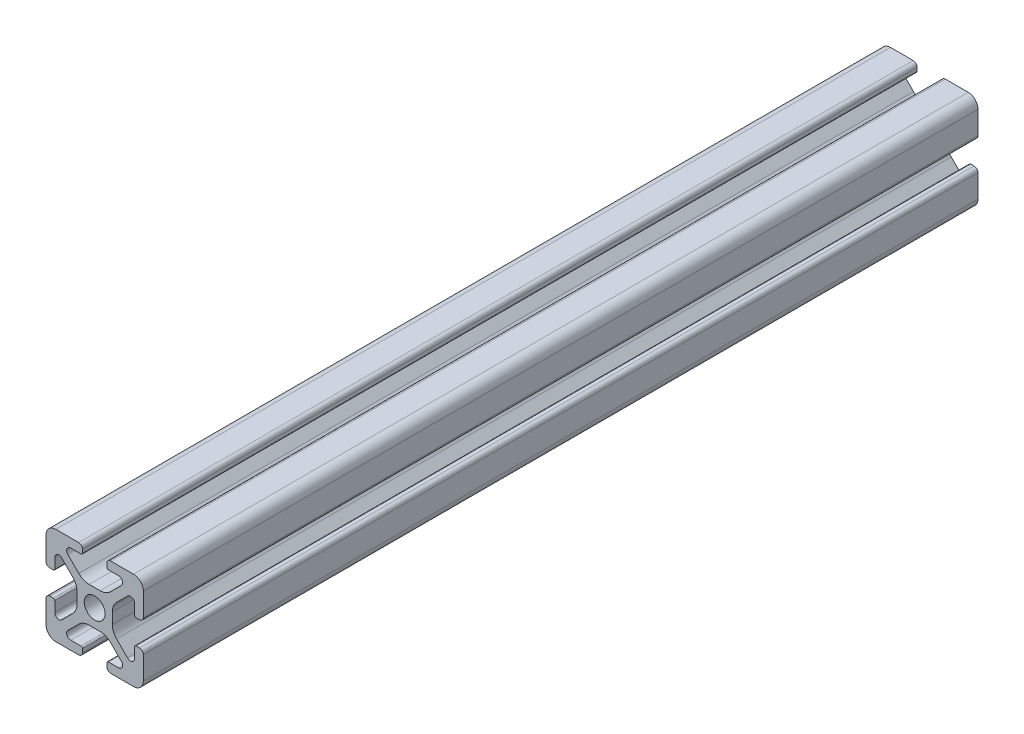
SolidWorks part; units mm, degrees
ref_plane "Front Plane" through (0, 0, 0) normal (0, 0, 1) x (1, 0, 0)
ref_plane "Top Plane" through (0, 0, 0) normal (0, 1, 0) x (1, 0, 0)
ref_plane "Right Plane" through (0, 0, 0) normal (1, 0, 0) x (0, 0, -1)
sketch "Sketch1" plane through (0, 0, 0) normal (0, 0, 1) x (1, 0, 0)
  line L2 (-9.9949, 7.9883) -> (-9.9949, 3.2893)
  line L3 (-7.9883, 9.9949) -> (-3.2893, 9.9949)
  line L4 (-2.5019, 9.2075) -> (-2.5019, 8.4963)
  line L5 (-2.8067, 8.1915) -> (-4.9149, 8.1915)
  line L6 (-5.5076, 6.7606) -> (-3.2528, 4.5058)
  line L7 (-6.7606, 5.5076) -> (-4.5058, 3.2528)
  line L8 (-8.1915, 4.9149) -> (-8.1915, 2.8067)
  line L9 (-8.4963, 2.5019) -> (-9.2075, 2.5019)
  line L11 (-1.1334, 3.6279) -> (1.1334, 3.6279)
  line L12 (-3.6279, 1.1334) -> (-3.6279, -1.1334)
  line L13 (8.4963, 2.5019) -> (9.2075, 2.5019)
  line L14 (8.1915, 4.9149) -> (8.1915, 2.8067)
  line L15 (9.9949, 7.9883) -> (9.9949, 3.2893)
  line L16 (7.9883, 9.9949) -> (3.2893, 9.9949)
  line L17 (2.5019, 9.2075) -> (2.5019, 8.4963)
  line L18 (2.8067, 8.1915) -> (4.9149, 8.1915)
  line L19 (3.6279, 1.1334) -> (3.6279, -1.1334)
  line L20 (5.5076, 6.7606) -> (3.2528, 4.5058)
  line L21 (6.7606, 5.5076) -> (4.5058, 3.2528)
  line L22 (-8.4963, -2.5019) -> (-9.2075, -2.5019)
  line L23 (-8.1915, -4.9149) -> (-8.1915, -2.8067)
  line L24 (-6.7606, -5.5076) -> (-4.5058, -3.2528)
  line L25 (-5.5076, -6.7606) -> (-3.2528, -4.5058)
  line L26 (-2.8067, -8.1915) -> (-4.9149, -8.1915)
  line L27 (-2.5019, -9.2075) -> (-2.5019, -8.4963)
  line L28 (-7.9883, -9.9949) -> (-3.2893, -9.9949)
  line L29 (-9.9949, -7.9883) -> (-9.9949, -3.2893)
  line L30 (9.9949, -7.9883) -> (9.9949, -3.2893)
  line L31 (7.9883, -9.9949) -> (3.2893, -9.9949)
  line L32 (2.5019, -9.2075) -> (2.5019, -8.4963)
  line L33 (2.8067, -8.1915) -> (4.9149, -8.1915)
  line L34 (5.5076, -6.7606) -> (3.2528, -4.5058)
  line L35 (6.7606, -5.5076) -> (4.5058, -3.2528)
  line L36 (8.1915, -4.9149) -> (8.1915, -2.8067)
  line L37 (8.4963, -2.5019) -> (9.2075, -2.5019)
  line L38 (-1.1334, -3.6279) -> (1.1334, -3.6279)
  circle A0 centre (0, 0) radius 2.1463
  arc A1 (-9.9949, 7.9883) -> (-7.9883, 9.9949) centre (-7.9883, 7.9883) cw
  arc A2 (-6.7606, 5.5076) -> (-8.1915, 4.9149) centre (-7.3533, 4.9149) ccw
  arc A3 (-4.9149, 8.1915) -> (-5.5076, 6.7606) centre (-4.9149, 7.3533) ccw
  arc A4 (-3.2893, 9.9949) -> (-2.5019, 9.2075) centre (-3.2893, 9.2075) cw
  arc A5 (-9.9949, 3.2893) -> (-9.2075, 2.5019) centre (-9.2075, 3.2893) ccw
  arc A6 (-8.1915, 2.8067) -> (-8.4963, 2.5019) centre (-8.4963, 2.8067) cw
  arc A7 (-2.5019, 8.4963) -> (-2.8067, 8.1915) centre (-2.8067, 8.4963) cw
  arc A8 (-1.1334, 3.6279) -> (-3.2528, 4.5058) centre (-1.1334, 6.6251) cw
  arc A9 (-3.6279, 1.1334) -> (-4.5058, 3.2528) centre (-6.6251, 1.1334) ccw
  arc A10 (8.1915, 2.8067) -> (8.4963, 2.5019) centre (8.4963, 2.8067) ccw
  arc A11 (9.9949, 3.2893) -> (9.2075, 2.5019) centre (9.2075, 3.2893) cw
  arc A12 (9.9949, 7.9883) -> (7.9883, 9.9949) centre (7.9883, 7.9883) ccw
  arc A13 (3.2893, 9.9949) -> (2.5019, 9.2075) centre (3.2893, 9.2075) ccw
  arc A14 (2.5019, 8.4963) -> (2.8067, 8.1915) centre (2.8067, 8.4963) ccw
  arc A15 (1.1334, 3.6279) -> (3.2528, 4.5058) centre (1.1334, 6.6251) ccw
  arc A16 (3.6279, 1.1334) -> (4.5058, 3.2528) centre (6.6251, 1.1334) cw
  arc A17 (6.7606, 5.5076) -> (8.1915, 4.9149) centre (7.3533, 4.9149) cw
  arc A18 (4.9149, 8.1915) -> (5.5076, 6.7606) centre (4.9149, 7.3533) cw
  arc A19 (-3.6279, -1.1334) -> (-4.5058, -3.2528) centre (-6.6251, -1.1334) cw
  arc A20 (-1.1334, -3.6279) -> (-3.2528, -4.5058) centre (-1.1334, -6.6251) ccw
  arc A21 (-2.5019, -8.4963) -> (-2.8067, -8.1915) centre (-2.8067, -8.4963) ccw
  arc A22 (-8.1915, -2.8067) -> (-8.4963, -2.5019) centre (-8.4963, -2.8067) ccw
  arc A23 (-9.9949, -3.2893) -> (-9.2075, -2.5019) centre (-9.2075, -3.2893) cw
  arc A24 (-3.2893, -9.9949) -> (-2.5019, -9.2075) centre (-3.2893, -9.2075) ccw
  arc A25 (-4.9149, -8.1915) -> (-5.5076, -6.7606) centre (-4.9149, -7.3533) cw
  arc A26 (-6.7606, -5.5076) -> (-8.1915, -4.9149) centre (-7.3533, -4.9149) cw
  arc A27 (-9.9949, -7.9883) -> (-7.9883, -9.9949) centre (-7.9883, -7.9883) ccw
  arc A28 (9.9949, -7.9883) -> (7.9883, -9.9949) centre (7.9883, -7.9883) cw
  arc A29 (6.7606, -5.5076) -> (8.1915, -4.9149) centre (7.3533, -4.9149) ccw
  arc A30 (4.9149, -8.1915) -> (5.5076, -6.7606) centre (4.9149, -7.3533) ccw
  arc A31 (3.2893, -9.9949) -> (2.5019, -9.2075) centre (3.2893, -9.2075) cw
  arc A32 (9.9949, -3.2893) -> (9.2075, -2.5019) centre (9.2075, -3.2893) ccw
  arc A33 (8.1915, -2.8067) -> (8.4963, -2.5019) centre (8.4963, -2.8067) cw
  arc A34 (2.5019, -8.4963) -> (2.8067, -8.1915) centre (2.8067, -8.4963) cw
  arc A35 (1.1334, -3.6279) -> (3.2528, -4.5058) centre (1.1334, -6.6251) cw
  arc A36 (3.6279, -1.1334) -> (4.5058, -3.2528) centre (6.6251, -1.1334) ccw
extrude "Boss-Extrude1" add sketch "Sketch1" along normal mid plane 171.45
